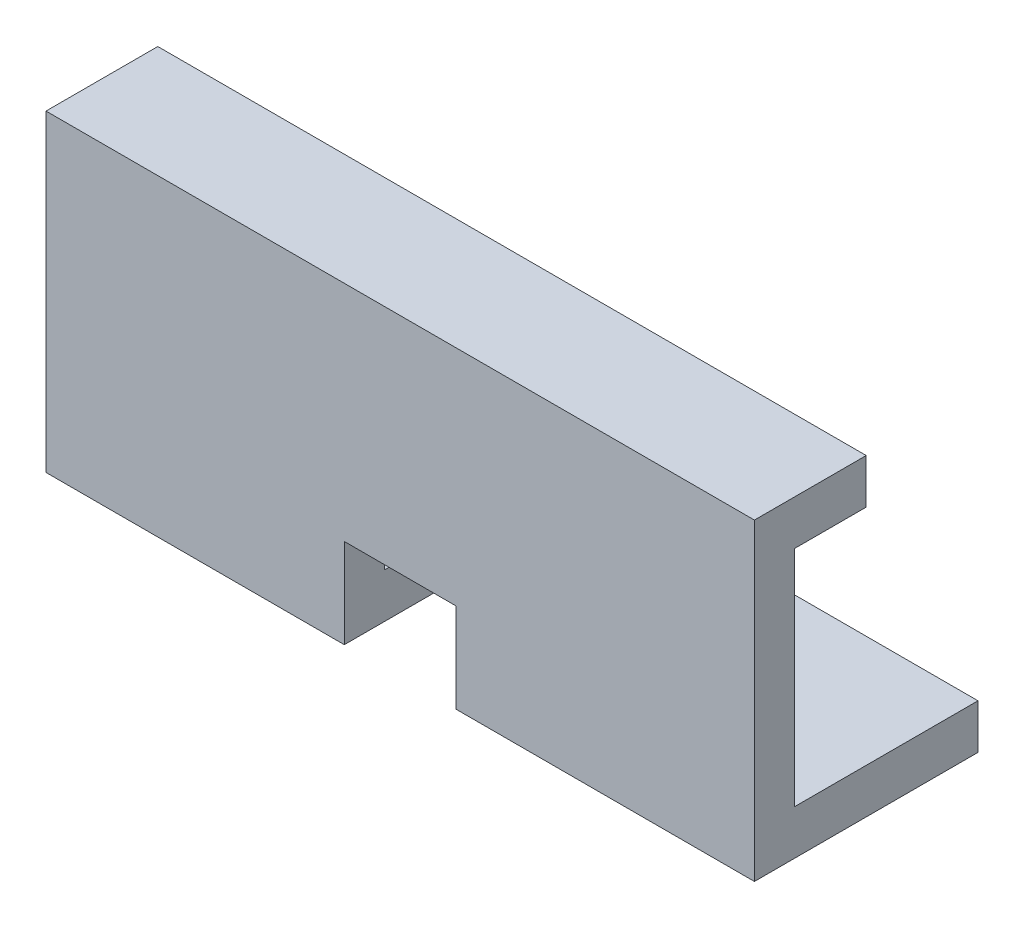
SolidWorks part; units mm, degrees
ref_plane "Alzado" through (0, 0, 0) normal (0, 0, 1) x (1, 0, 0)
ref_plane "Planta" through (0, 0, 0) normal (0, 1, 0) x (1, 0, 0)
ref_plane "Vista lateral" through (0, 0, 0) normal (1, 0, 0) x (0, 0, -1)
sketch "Croquis2" plane through (0, 0, 0) normal (0, 1, 0) x (1, 0, 0)
  line L0 (0, 5) -> (3.8426, 5) construction
  line L1 (0, 0) -> (21.6851, 0)
  line L2 (0, 0) -> (0, 10)
  line L3 (0, 10) -> (21.6851, 10)
  line L4 (21.6851, 0) -> (21.6851, 10)
  line L5 (3.8426, 5) -> (17.8426, 5) construction
  line L6 (17.8426, 5) -> (21.6851, 5) construction
  circle A0 centre (3.8426, 5) radius 1.5
  circle A1 centre (17.8426, 5) radius 1.5
  dimension "D1" = 14
  dimension "D4" = 3
  dimension "D2" = 5
  dimension "D3" = 10
extrude "Saliente-Extruir1" add sketch "Croquis2" along normal blind 2
sketch "Croquis3" plane through (0, 2, 0) normal (0, 1, 0) x (1, 0, 0)
  line L0 (21.6851, 0) -> (21.6851, 10) construction
  line L1 (0, 0) -> (21.6851, 0)
  line L2 (0, 0) -> (0, 1.8)
  line L3 (0, 1.8) -> (21.6851, 1.8)
  line L4 (21.6851, 0) -> (21.6851, 1.8)
  circle A0 centre (3.8426, 5) radius 2.85 construction
  dimension "D1" = 5.7
  dimension "D2" = 1.8
extrude "Saliente-Extruir2" add sketch "Croquis3" along normal blind 10
sketch "Croquis4" plane through (0, 2, 0) normal (0, 1, 0) x (1, 0, 0)
  line L1 (8.3426, 5) -> (13.3426, 5)
  line L2 (8.3426, 5) -> (8.3426, 0)
  line L3 (8.3426, 0) -> (13.3426, 0)
  line L4 (13.3426, 5) -> (13.3426, 0)
  line L5 (0, 0) -> (21.6851, 0) construction
  line L7 (10.8426, 5) -> (10.8426, 10) construction
  line L8 (21.6851, 10) -> (0, 10) construction
  dimension "D1" = 5
  dimension "D2" = 5
extrude "Cortar-Extruir1" cut sketch "Croquis4" against normal blind 10 and the other way blind 2
sketch "Croquis7" plane through (0, 12, 0) normal (0, 1, 0) x (1, 0, 0)
  line L0 (21.6851, 1.8) -> (21.6851, 10) construction
  line L1 (0, 0) -> (21.6851, 0)
  line L2 (0, 0) -> (0, 5)
  line L3 (0, 5) -> (21.6851, 5)
  line L4 (21.6851, 0) -> (21.6851, 5)
  dimension "D1" = 5
extrude "Saliente-Extruir4" add sketch "Croquis7" along normal blind 2
sketch "Croquis8" plane through (0, 0, 0) normal (-1, 0, 0) x (0, 0, 1)
  line L8 (-10, 0) -> (0, 0)
  line L9 (0, 0) -> (0, 14)
  line L10 (0, 14) -> (-5, 14)
  line L11 (-5, 14) -> (-5, 12)
  line L12 (-5, 12) -> (-1.8, 12)
  line L13 (-1.8, 12) -> (-1.8, 2)
  line L14 (-1.8, 2) -> (-10, 2)
  line L15 (-10, 2) -> (-10, 0)
  line L16 (-10, 0) -> (0, 0)
  line L17 (0, 0) -> (0, 14)
  line L18 (0, 14) -> (-5, 14)
  line L19 (-5, 14) -> (-5, 12)
  line L20 (-5, 12) -> (-1.8, 12)
  line L21 (-1.8, 12) -> (-1.8, 2)
  line L22 (-1.8, 2) -> (-10, 2)
  line L23 (-10, 2) -> (-10, 0)
  dimension "D1" = 0
extrude "Saliente-Extruir5" add sketch "Croquis8" along normal blind 5
sketch "Croquis9" plane through (21.6851, 0, 0) normal (1, 0, 0) x (0, 0, -1)
  line L8 (0, 0) -> (10, 0)
  line L9 (10, 0) -> (10, 2)
  line L10 (10, 2) -> (1.8, 2)
  line L11 (1.8, 2) -> (1.8, 12)
  line L12 (1.8, 12) -> (5, 12)
  line L13 (5, 12) -> (5, 14)
  line L14 (5, 14) -> (0, 14)
  line L15 (0, 14) -> (0, 0)
  line L16 (0, 0) -> (10, 0)
  line L17 (10, 0) -> (10, 2)
  line L18 (10, 2) -> (1.8, 2)
  line L19 (1.8, 2) -> (1.8, 12)
  line L20 (1.8, 12) -> (5, 12)
  line L21 (5, 12) -> (5, 14)
  line L22 (5, 14) -> (0, 14)
  line L23 (0, 14) -> (0, 0)
  dimension "D1" = 0
extrude "Saliente-Extruir6" add sketch "Croquis9" along normal blind 5
